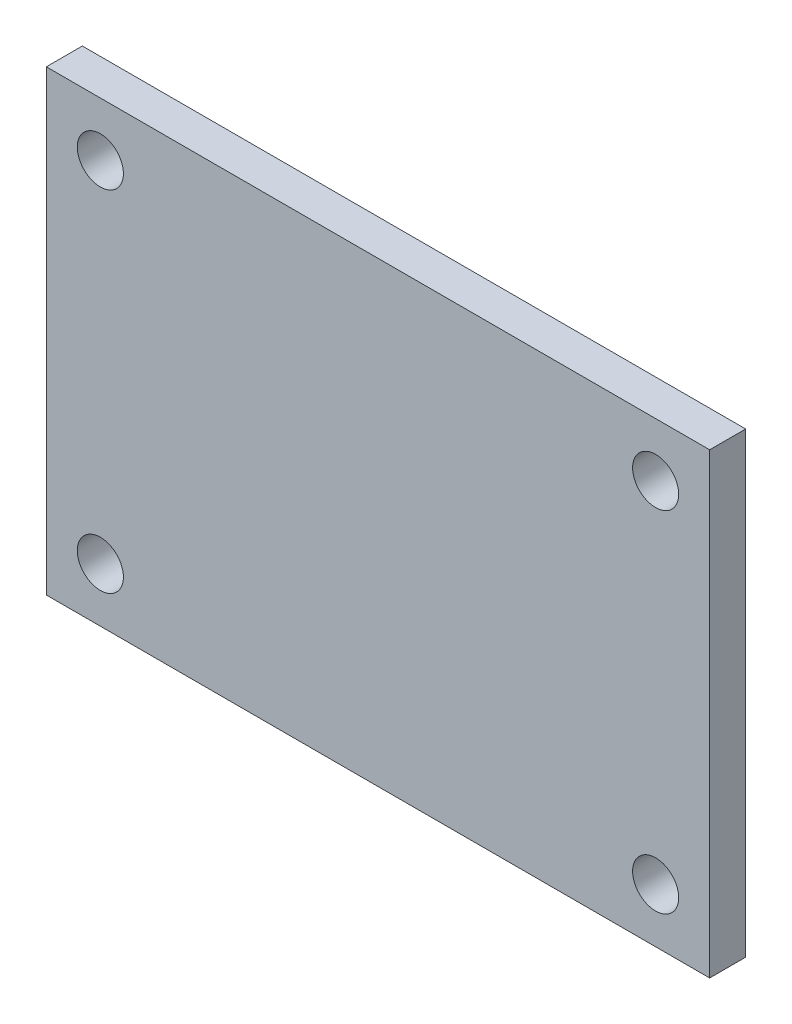
SolidWorks part; units mm, degrees
ref_plane "Plan de face" through (0, 0, 0) normal (0, 0, 1) x (1, 0, 0)
ref_plane "Plan de dessus" through (0, 0, 0) normal (0, 1, 0) x (1, 0, 0)
ref_plane "Plan de droite" through (0, 0, 0) normal (1, 0, 0) x (0, 0, -1)
sketch "Esquisse1" plane through (0, 0, 0) normal (0, 0, 1) x (1, 0, 0)
  line L2 (0, 0) -> (-92.08, 0)
  line L3 (-92.08, 0) -> (-92.08, -63.5)
  line L4 (-92.08, -63.5) -> (0, -63.5)
  line L5 (0, -63.5) -> (0, 0)
  line L12 (-84.58, -56) -> (-7.5, -56) construction
  line L13 (-84.58, -56) -> (-84.58, -7.5) construction
  line L14 (-84.58, -7.5) -> (-7.5, -7.5) construction
  line L15 (-7.5, -56) -> (-7.5, -7.5) construction
  line L16 (-46.04, -7.5) -> (-46.04, -56) construction
  line L17 (-84.58, -31.75) -> (-7.5, -31.75) construction
  circle A8 centre (-84.58, -7.5) radius 3.2
  circle A9 centre (-7.5, -7.5) radius 3.2
  circle A10 centre (-7.5, -56) radius 3.2
  circle A11 centre (-84.58, -56) radius 3.2
  point P2 (-46.04, -31.75)
  point P28 (0, 0)
  point P29 (0, 0)
  point P30 (0, 0)
  dimension "D1" = 6.4
  dimension "D2" = 7.5
  dimension "D3" = 7.5
  dimension "D4" = 7.5
  dimension "D5" = 7.5
  dimension "D6" = 92.08
  dimension "D7" = 63.5
extrude "Boss.-Extru.1" add sketch "Esquisse1" along normal blind 5
